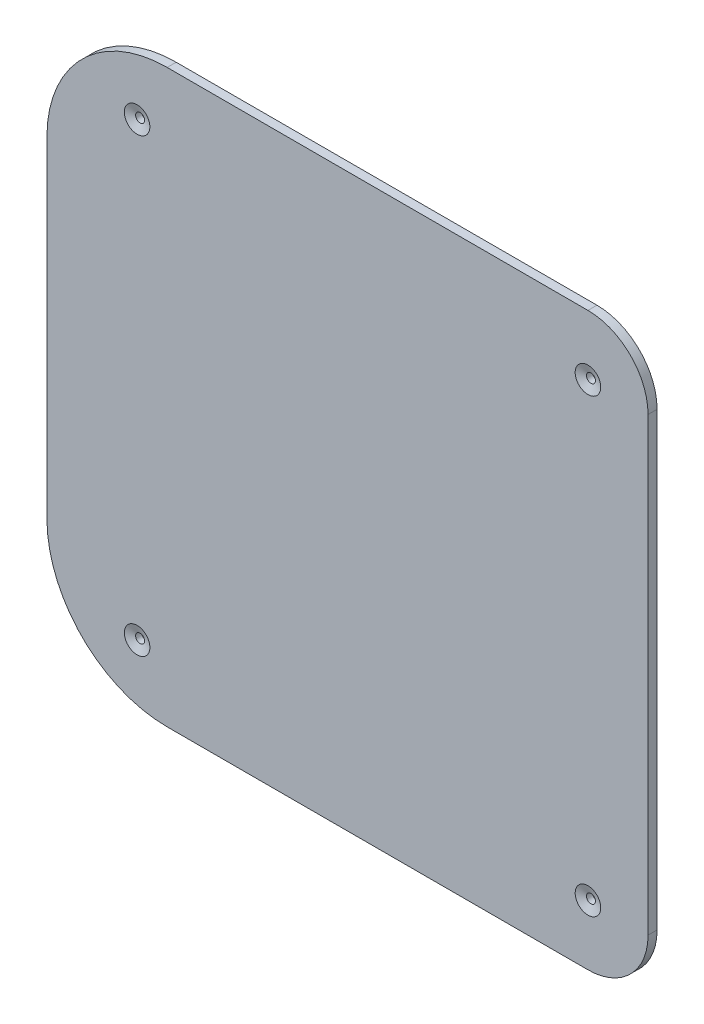
SolidWorks part; units mm, degrees
ref_plane "Front Plane" through (0, 0, 0) normal (0, 0, 1) x (1, 0, 0)
ref_plane "Top Plane" through (0, 0, 0) normal (0, 1, 0) x (1, 0, 0)
ref_plane "Right Plane" through (0, 0, 0) normal (1, 0, 0) x (0, 0, -1)
sketch "Sketch1" plane through (0, 0, 0) normal (0, 0, 1) x (1, 0, 0)
  line L0 (0, 0) -> (-100, 0) construction
  line L4 (80, 95) -> (-60, 95)
  line L5 (100, -75) -> (100, 75)
  line L6 (-60, -95) -> (80, -95)
  line L7 (-100, 55) -> (-100, -55)
  arc A4 (100, 75) -> (80, 95) centre (80, 75) ccw
  arc A5 (80, -95) -> (100, -75) centre (80, -75) ccw
  arc A6 (-100, -55) -> (-60, -95) centre (-60, -55) ccw
  arc A7 (-60, 95) -> (-100, 55) centre (-60, 55) ccw
  dimension "D2" = 20
  dimension "D3" = 40
  dimension "D1" = 200
  dimension "D4" = 100
  dimension "D5" = 190
extrude "base" add sketch "Sketch1" along normal blind 3
sketch "Sketch2" plane through (0, 0, 0) normal (0, 0, -1) x (-1, 0, 0)
  line L0 (-80, 75) -> (-80, -75) construction
  line L1 (-100, -75) -> (-100, 75) construction
  line L4 (-80, 75) -> (70, 75) construction
  line L5 (70, 75) -> (70, -75) construction
  line L6 (70, -75) -> (-80, -75) construction
  line L7 (-80, 0) -> (-100, 0) construction
  line L8 (-5, 75) -> (-5, 95) construction
  line L9 (-80, 95) -> (60, 95) construction
  line L10 (70, 0) -> (100, 0) construction
  line L11 (100, 55) -> (100, -55) construction
  circle A4 centre (-80, 75) radius 1.5
  circle A5 centre (-80, -75) radius 1.5
  circle A6 centre (70, -75) radius 1.5
  circle A7 centre (70, 75) radius 1.5
  dimension "D4" = 3
  dimension "D1" = 20
  dimension "D2" = 30
extrude "screwHoles" cut sketch "Sketch2" against normal through all
chamfer "Chamfer1" distance 1 angle 70 4 edges at (-71.5, -75, 3) (78.5, -75, 3) (78.5, 75, 3) (-71.5, 75, 3)
sketch "Sketch3" plane through (0, 0, 0) normal (0, 0, -1) x (-1, 0, 0)
  line L0 (-100, 0) -> (0, 0) construction
  line L1 (-100, -75) -> (-100, 75) construction
  line L2 (-81, 15.5) -> (-81, -39.5)
  line L3 (-81, 15.5) -> (-71, 15.5)
  line L4 (-71, 15.5) -> (-71, -39.5)
  line L5 (-71, -39.5) -> (-81, -39.5)
  line L6 (-71, 15.5) -> (-38.5, 15.5) construction
  line L7 (-38.5, 15.5) -> (-28.5, 15.5)
  line L8 (-28.5, 15.5) -> (-28.5, -39.5)
  line L9 (-28.5, -39.5) -> (-38.5, -39.5)
  line L10 (-38.5, -39.5) -> (-71, -39.5) construction
  line L11 (-38.5, 15.5) -> (-38.5, -39.5)
  dimension "D1" = 15.5
  dimension "D2" = 55
  dimension "D3" = 19
  dimension "D4" = 10
  dimension "D5" = 32.5
extrude "arduinoRisers" add sketch "Sketch3" along normal blind 4
sketch "Sketch4" plane through (0, 0, 0) normal (0, 0, -1) x (-1, 0, 0)
  line L0 (-71, -39.5) -> (-71, 15.5) construction
  line L1 (-81, -39.5) -> (-71, -39.5)
  line L2 (-81, -39.5) -> (-81, -41)
  line L3 (-81, -41) -> (-71, -41)
  line L4 (-71, -39.5) -> (-71, -41)
  line L5 (-38.5, -39.5) -> (-28.5, -39.5)
  line L6 (-38.5, -39.5) -> (-38.5, -41)
  line L7 (-38.5, -41) -> (-28.5, -41)
  line L8 (-28.5, -39.5) -> (-28.5, -41)
  line L9 (-81, 15.5) -> (-71, 15.5)
  line L10 (-81, 15.5) -> (-81, 17)
  line L11 (-81, 17) -> (-71, 17)
  line L12 (-71, 15.5) -> (-71, 17)
  line L13 (-38.5, 15.5) -> (-28.5, 15.5)
  line L14 (-38.5, 15.5) -> (-38.5, 17)
  line L15 (-38.5, 17) -> (-28.5, 17)
  line L16 (-28.5, 15.5) -> (-28.5, 17)
  dimension "D1" = 1.5
extrude "arduinoClampsSide" add sketch "Sketch4" along normal blind 10
sketch "Sketch5" plane through (81, 0, 0) normal (1, 0, 0) x (0, 0, -1)
  line L0 (5, 15.5) -> (8.7127, 14.3862)
  line L1 (10, 15.5) -> (4, 15.5) construction
  line L2 (10, 15.344) -> (10, 15.5)
  line L3 (10, 15.5) -> (5, 15.5)
  line L4 (10, 17) -> (10, 15.5) construction
  line L5 (5, -39.5) -> (8.7127, -38.3862)
  line L6 (10, -39.5) -> (4, -39.5) construction
  line L7 (10, -39.344) -> (10, -39.5)
  line L8 (10, -39.5) -> (5, -39.5)
  arc A0 (8.7127, 14.3862) -> (10, 15.344) centre (9, 15.344) ccw
  arc A1 (8.7127, -38.3862) -> (10, -39.344) centre (9, -39.344) cw
  point P11 (10, 14)
  dimension "D3" = 1
  dimension "D4" = 1
  dimension "D1" = 1
  dimension "D2" = 1.5
extrude "arduinoClampsCatchers1" add sketch "Sketch5" against normal up to surface (10 mm away) up to face at (71, -12, -6)
sketch "Sketch6" plane through (38.5, 0, 0) normal (1, 0, 0) x (0, 0, -1)
  line L3 (5, 15.5) -> (8.7127, 14.3862)
  line L4 (10, 15.344) -> (10, 15.5)
  line L5 (10, 15.5) -> (5, 15.5)
  line L6 (5, 15.5) -> (8.7127, 14.3862)
  line L7 (10, 15.344) -> (10, 15.5)
  line L8 (10, 15.5) -> (5, 15.5)
  line L9 (8.7127, -38.3862) -> (5, -39.5)
  line L10 (5, -39.5) -> (10, -39.5)
  line L11 (10, -39.5) -> (10, -39.344)
  line L12 (8.7127, -38.3862) -> (5, -39.5)
  line L13 (5, -39.5) -> (10, -39.5)
  line L14 (10, -39.5) -> (10, -39.344)
  arc A1 (8.7127, 14.3862) -> (10, 15.344) centre (9, 15.344) ccw
  arc A2 (8.7127, 14.3862) -> (10, 15.344) centre (9, 15.344) ccw
  arc A3 (10, -39.344) -> (8.7127, -38.3862) centre (9, -39.344) ccw
  arc A4 (10, -39.344) -> (8.7127, -38.3862) centre (9, -39.344) ccw
  dimension "D1" = 0
  dimension "D2" = 0
extrude "arduinoClampsCatchers2" add sketch "Sketch6" against normal up to surface (10 mm away) up to face at (28.5, -12, -6)
sketch "Sketch7" plane through (0, 0, -4) normal (0, 0, -1) x (-1, 0, 0)
  line L0 (-28.5, -39.5) -> (-28.5, 15.5) construction
  line L1 (-28.5, -5.5) -> (-38.5, -5.5)
  line L2 (-28.5, -5.5) -> (-28.5, -16.5)
  line L3 (-28.5, -16.5) -> (-38.5, -16.5)
  line L4 (-38.5, -5.5) -> (-38.5, -16.5)
  line L5 (-38.5, 15.5) -> (-38.5, -39.5) construction
  line L6 (-28.5, 15.5) -> (-38.5, 15.5) construction
  line L7 (-38.5, -39.5) -> (-28.5, -39.5) construction
  dimension "D1" = 21
  dimension "D2" = 23
extrude "ISPspace" cut sketch "Sketch7" against normal up to surface (4 mm away) up to face at (76, -12, 0)
